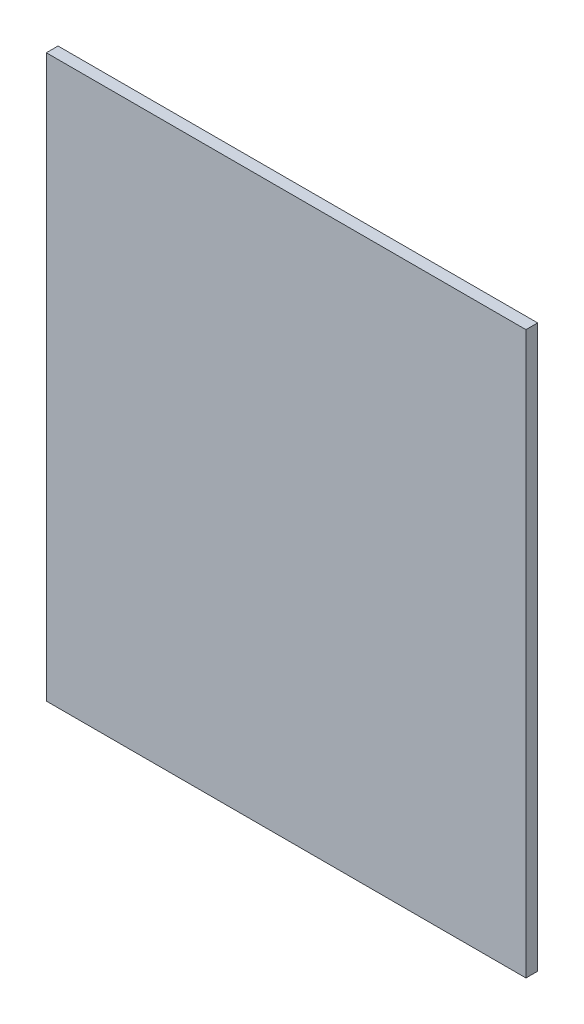
SolidWorks part; units mm, degrees
ref_plane "Front Plane" through (0, 0, 0) normal (0, 0, 1) x (1, 0, 0)
ref_plane "Top Plane" through (0, 0, 0) normal (0, 1, 0) x (1, 0, 0)
ref_plane "Right Plane" through (0, 0, 0) normal (1, 0, 0) x (0, 0, -1)
sketch "Sketch1" plane through (0, 0, 0) normal (0, 0, 1) x (1, 0, 0)
  line L1 (-19.05, -285.75) -> (241.3, -285.75)
  line L2 (-19.05, -285.75) -> (-19.05, 19.05)
  line L3 (-19.05, 19.05) -> (241.3, 19.05)
  line L4 (241.3, -285.75) -> (241.3, 19.05)
  line L5 (-19.05, -285.75) -> (241.3, 19.05) construction
  line L6 (-19.05, 19.05) -> (241.3, -285.75) construction
  circle A0 centre (-9.525, -276.225) radius 2.75
  circle A1 centre (231.7912, -276.225) radius 2.7338
  circle A2 centre (231.775, 9.525) radius 2.75
  circle A3 centre (-9.525, 9.525) radius 2.75
  circle A4 centre (231.775, 9.525) radius 2.75 construction
  point P4 (111.125, -133.35)
extrude "Boss-Extrude1" add sketch "Sketch1" along normal blind 6.35 contours L3 L4 L1 L2
